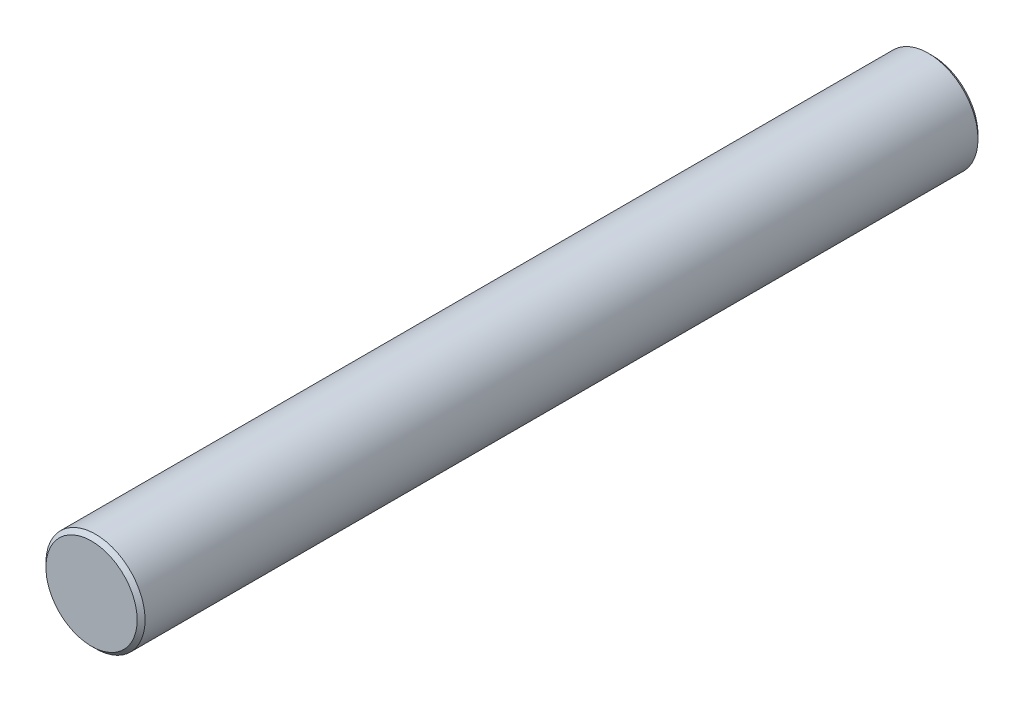
SolidWorks part; units mm, degrees
material "普通碳钢"
ref_plane "前视基准面" through (0, 0, 0) normal (0, 0, 1) x (1, 0, 0)
ref_plane "上视基准面" through (0, 0, 0) normal (0, 1, 0) x (1, 0, 0)
ref_plane "右视基准面" through (0, 0, 0) normal (1, 0, 0) x (0, 0, -1)
sketch "草图1" plane through (0, 0, 0) normal (0, 0, 1) x (1, 0, 0)
  line L0 (-87.1056, 0) -> (87.1056, 0) construction
  line L1 (0, 87.1056) -> (0, -87.1056) construction
  circle A0 centre (0, 0) radius 12.5
  dimension "D1" = 25
extrude "凸台-拉伸1" add sketch "草图1" along normal mid plane 212
chamfer "倒角1" distance 1 angle 45 2 edges at (12.5, 0, -106) (12.5, 0, 106)
